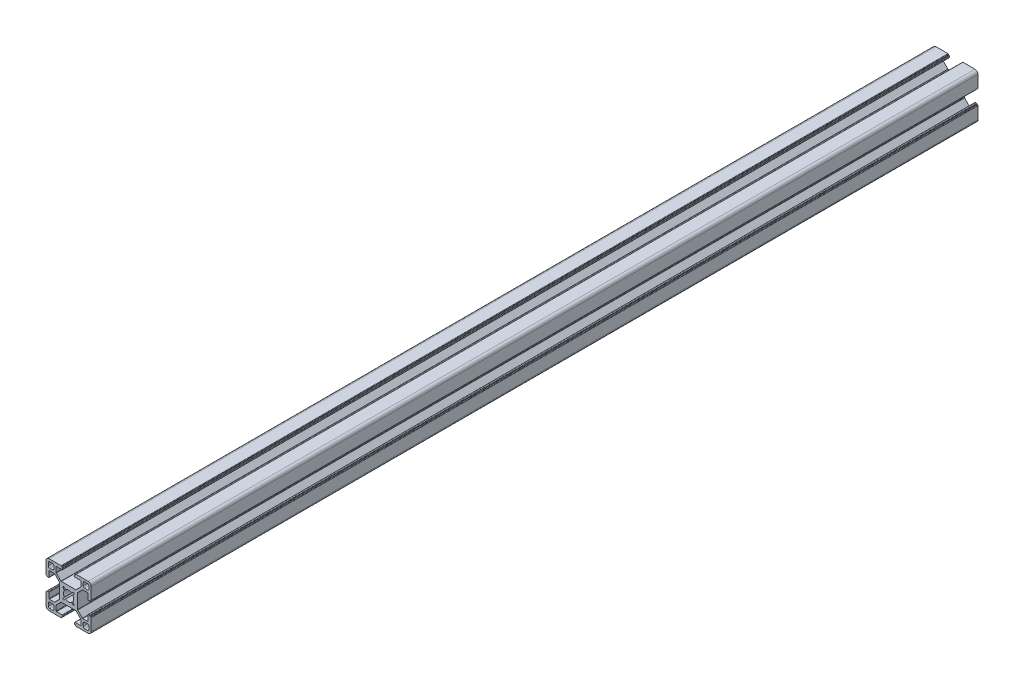
SolidWorks part; units mm, degrees
ref_plane "Piano frontale" through (0, 0, 0) normal (0, 0, 1) x (1, 0, 0)
ref_plane "Piano superiore" through (0, 0, 0) normal (0, 1, 0) x (1, 0, 0)
ref_plane "Piano destro" through (0, 0, 0) normal (1, 0, 0) x (0, 0, -1)
ref_plane "Piano1" through (0, 0, 25) normal (0, 0, 1) x (1, 0, 0)
sketch "Schizzo1" plane through (0, 0, 25) normal (0, 0, 1) x (1, 0, 0)
  line L0 (-12.5625, -9.75) -> (-10.6875, -9.75)
  line L1 (-9.75, -10.6875) -> (-9.75, -12.5625)
  line L2 (-10.6875, -13.5) -> (-12.5625, -13.5)
  line L3 (-13.5, -12.5625) -> (-13.5, -10.6875)
  line L4 (12.5625, 9.75) -> (10.6875, 9.75)
  line L5 (9.75, 10.6875) -> (9.75, 12.5625)
  line L6 (10.6875, 13.5) -> (12.5625, 13.5)
  line L7 (13.5, 12.5625) -> (13.5, 10.6875)
  line L8 (-4.7, -14.7) -> (-4.7, -14.6)
  line L9 (-4.4, -14.3) -> (-4.3, -14.3)
  line L10 (-4, -14) -> (-4, -13.3)
  line L11 (-4.3, -13) -> (-7.95, -13)
  line L12 (-8.25, -12.7) -> (-8.25, -9.4349)
  line L13 (-8.1621, -9.2228) -> (-5.0272, -6.0879)
  line L14 (-4.8151, -6) -> (4.8151, -6)
  line L15 (5.0272, -6.0879) -> (8.1621, -9.2228)
  line L16 (8.25, -9.4349) -> (8.25, -12.7)
  line L17 (7.95, -13) -> (4.3, -13)
  line L18 (4, -13.3) -> (4, -14)
  line L19 (4.3, -14.3) -> (4.4, -14.3)
  line L20 (4.7, -14.6) -> (4.7, -14.7)
  line L21 (5, -15) -> (13, -15)
  line L22 (15, -13) -> (15, -5)
  line L23 (14.7, -4.7) -> (14.6, -4.7)
  line L24 (14.3, -4.4) -> (14.3, -4.3)
  line L25 (14, -4) -> (13.3, -4)
  line L26 (13, -4.3) -> (13, -7.95)
  line L27 (12.7, -8.25) -> (9.4349, -8.25)
  line L28 (9.2228, -8.1621) -> (6.0879, -5.0272)
  line L29 (6, -4.8151) -> (6, 4.8151)
  line L30 (6.0879, 5.0272) -> (9.2228, 8.1621)
  line L31 (9.4349, 8.25) -> (12.7, 8.25)
  line L32 (13, 7.95) -> (13, 4.3)
  line L33 (13.3, 4) -> (14, 4)
  line L34 (14.3, 4.3) -> (14.3, 4.4)
  line L35 (14.6, 4.7) -> (14.7, 4.7)
  line L36 (15, 5) -> (15, 13)
  line L37 (13, 15) -> (5, 15)
  line L38 (4.7, 14.7) -> (4.7, 14.6)
  line L39 (4.4, 14.3) -> (4.3, 14.3)
  line L40 (4, 14) -> (4, 13.3)
  line L41 (4.3, 13) -> (7.95, 13)
  line L42 (8.25, 12.7) -> (8.25, 9.4349)
  line L43 (8.1621, 9.2228) -> (5.0272, 6.0879)
  line L44 (4.8151, 6) -> (-4.8151, 6)
  line L45 (-5.0272, 6.0879) -> (-8.1621, 9.2228)
  line L46 (-8.25, 9.4349) -> (-8.25, 12.7)
  line L47 (-7.95, 13) -> (-4.3, 13)
  line L48 (-4, 13.3) -> (-4, 14)
  line L49 (-4.3, 14.3) -> (-4.4, 14.3)
  line L50 (-4.7, 14.6) -> (-4.7, 14.7)
  line L51 (-5, 15) -> (-13, 15)
  line L52 (-15, 13) -> (-15, 5)
  line L53 (-14.7, 4.7) -> (-14.6, 4.7)
  line L54 (-14.3, 4.4) -> (-14.3, 4.3)
  line L55 (-14, 4) -> (-13.3, 4)
  line L56 (-13, 4.3) -> (-13, 7.95)
  line L57 (-12.7, 8.25) -> (-9.4349, 8.25)
  line L58 (-9.2228, 8.1621) -> (-6.0879, 5.0272)
  line L59 (-6, 4.8151) -> (-6, -4.8151)
  line L60 (-6.0879, -5.0272) -> (-9.2228, -8.1621)
  line L61 (-9.4349, -8.25) -> (-12.7, -8.25)
  line L62 (-13, -7.95) -> (-13, -4.3)
  line L63 (-13.3, -4) -> (-14, -4)
  line L64 (-14.3, -4.3) -> (-14.3, -4.4)
  line L65 (-14.6, -4.7) -> (-14.7, -4.7)
  line L66 (-15, -5) -> (-15, -13)
  line L67 (-13, -15) -> (-5, -15)
  line L68 (2.0101, 2.7422) -> (2.8679, 3.6)
  line L69 (3.6, 2.8679) -> (2.7422, 2.0101)
  line L70 (2.7422, -2.0101) -> (3.6, -2.8679)
  line L71 (2.8679, -3.6) -> (2.0101, -2.7422)
  line L72 (-2.0101, -2.7422) -> (-2.8679, -3.6)
  line L73 (-3.6, -2.8679) -> (-2.7422, -2.0101)
  line L74 (-2.7422, 2.0101) -> (-3.6, 2.8679)
  line L75 (-2.8679, 3.6) -> (-2.0101, 2.7422)
  line L76 (-9.75, 12.5625) -> (-9.75, 10.6875)
  line L77 (-10.6875, 9.75) -> (-12.5625, 9.75)
  line L78 (-13.5, 10.6875) -> (-13.5, 12.5625)
  line L79 (-12.5625, 13.5) -> (-10.6875, 13.5)
  line L80 (9.75, -12.5625) -> (9.75, -10.6875)
  line L81 (10.6875, -9.75) -> (12.5625, -9.75)
  line L82 (13.5, -10.6875) -> (13.5, -12.5625)
  line L83 (12.5625, -13.5) -> (10.6875, -13.5)
  arc A0 (-10.6875, -9.75) -> (-9.75, -10.6875) centre (-10.6875, -10.6875) cw
  arc A1 (-9.75, -12.5625) -> (-10.6875, -13.5) centre (-10.6875, -12.5625) cw
  arc A2 (-12.5625, -13.5) -> (-13.5, -12.5625) centre (-12.5625, -12.5625) cw
  arc A3 (-13.5, -10.6875) -> (-12.5625, -9.75) centre (-12.5625, -10.6875) cw
  arc A4 (10.6875, 9.75) -> (9.75, 10.6875) centre (10.6875, 10.6875) cw
  arc A5 (9.75, 12.5625) -> (10.6875, 13.5) centre (10.6875, 12.5625) cw
  arc A6 (12.5625, 13.5) -> (13.5, 12.5625) centre (12.5625, 12.5625) cw
  arc A7 (13.5, 10.6875) -> (12.5625, 9.75) centre (12.5625, 10.6875) cw
  arc A8 (-5, -15) -> (-4.7, -14.7) centre (-5, -14.7) ccw
  arc A9 (-4.7, -14.6) -> (-4.4, -14.3) centre (-4.4, -14.6) cw
  arc A10 (-4.3, -14.3) -> (-4, -14) centre (-4.3, -14) ccw
  arc A11 (-4, -13.3) -> (-4.3, -13) centre (-4.3, -13.3) ccw
  arc A12 (-7.95, -13) -> (-8.25, -12.7) centre (-7.95, -12.7) cw
  arc A13 (-8.25, -9.4349) -> (-8.1621, -9.2228) centre (-7.95, -9.4349) cw
  arc A14 (-5.0272, -6.0879) -> (-4.8151, -6) centre (-4.8151, -6.3) cw
  arc A15 (4.8151, -6) -> (5.0272, -6.0879) centre (4.8151, -6.3) cw
  arc A16 (8.1621, -9.2228) -> (8.25, -9.4349) centre (7.95, -9.4349) cw
  arc A17 (8.25, -12.7) -> (7.95, -13) centre (7.95, -12.7) cw
  arc A18 (4.3, -13) -> (4, -13.3) centre (4.3, -13.3) ccw
  arc A19 (4, -14) -> (4.3, -14.3) centre (4.3, -14) ccw
  arc A20 (4.4, -14.3) -> (4.7, -14.6) centre (4.4, -14.6) cw
  arc A21 (4.7, -14.7) -> (5, -15) centre (5, -14.7) ccw
  arc A22 (13, -15) -> (15, -13) centre (13, -13) ccw
  arc A23 (15, -5) -> (14.7, -4.7) centre (14.7, -5) ccw
  arc A24 (14.6, -4.7) -> (14.3, -4.4) centre (14.6, -4.4) cw
  arc A25 (14.3, -4.3) -> (14, -4) centre (14, -4.3) ccw
  arc A26 (13.3, -4) -> (13, -4.3) centre (13.3, -4.3) ccw
  arc A27 (13, -7.95) -> (12.7, -8.25) centre (12.7, -7.95) cw
  arc A28 (9.4349, -8.25) -> (9.2228, -8.1621) centre (9.4349, -7.95) cw
  arc A29 (6.0879, -5.0272) -> (6, -4.8151) centre (6.3, -4.8151) cw
  arc A30 (6, 4.8151) -> (6.0879, 5.0272) centre (6.3, 4.8151) cw
  arc A31 (9.2228, 8.1621) -> (9.4349, 8.25) centre (9.4349, 7.95) cw
  arc A32 (12.7, 8.25) -> (13, 7.95) centre (12.7, 7.95) cw
  arc A33 (13, 4.3) -> (13.3, 4) centre (13.3, 4.3) ccw
  arc A34 (14, 4) -> (14.3, 4.3) centre (14, 4.3) ccw
  arc A35 (14.3, 4.4) -> (14.6, 4.7) centre (14.6, 4.4) cw
  arc A36 (14.7, 4.7) -> (15, 5) centre (14.7, 5) ccw
  arc A37 (15, 13) -> (13, 15) centre (13, 13) ccw
  arc A38 (5, 15) -> (4.7, 14.7) centre (5, 14.7) ccw
  arc A39 (4.7, 14.6) -> (4.4, 14.3) centre (4.4, 14.6) cw
  arc A40 (4.3, 14.3) -> (4, 14) centre (4.3, 14) ccw
  arc A41 (4, 13.3) -> (4.3, 13) centre (4.3, 13.3) ccw
  arc A42 (7.95, 13) -> (8.25, 12.7) centre (7.95, 12.7) cw
  arc A43 (8.25, 9.4349) -> (8.1621, 9.2228) centre (7.95, 9.4349) cw
  arc A44 (5.0272, 6.0879) -> (4.8151, 6) centre (4.8151, 6.3) cw
  arc A45 (-4.8151, 6) -> (-5.0272, 6.0879) centre (-4.8151, 6.3) cw
  arc A46 (-8.1621, 9.2228) -> (-8.25, 9.4349) centre (-7.95, 9.4349) cw
  arc A47 (-8.25, 12.7) -> (-7.95, 13) centre (-7.95, 12.7) cw
  arc A48 (-4.3, 13) -> (-4, 13.3) centre (-4.3, 13.3) ccw
  arc A49 (-4, 14) -> (-4.3, 14.3) centre (-4.3, 14) ccw
  arc A50 (-4.4, 14.3) -> (-4.7, 14.6) centre (-4.4, 14.6) cw
  arc A51 (-4.7, 14.7) -> (-5, 15) centre (-5, 14.7) ccw
  arc A52 (-13, 15) -> (-15, 13) centre (-13, 13) ccw
  arc A53 (-15, 5) -> (-14.7, 4.7) centre (-14.7, 5) ccw
  arc A54 (-14.6, 4.7) -> (-14.3, 4.4) centre (-14.6, 4.4) cw
  arc A55 (-14.3, 4.3) -> (-14, 4) centre (-14, 4.3) ccw
  arc A56 (-13.3, 4) -> (-13, 4.3) centre (-13.3, 4.3) ccw
  arc A57 (-13, 7.95) -> (-12.7, 8.25) centre (-12.7, 7.95) cw
  arc A58 (-9.4349, 8.25) -> (-9.2228, 8.1621) centre (-9.4349, 7.95) cw
  arc A59 (-6.0879, 5.0272) -> (-6, 4.8151) centre (-6.3, 4.8151) cw
  arc A60 (-6, -4.8151) -> (-6.0879, -5.0272) centre (-6.3, -4.8151) cw
  arc A61 (-9.2228, -8.1621) -> (-9.4349, -8.25) centre (-9.4349, -7.95) cw
  arc A62 (-12.7, -8.25) -> (-13, -7.95) centre (-12.7, -7.95) cw
  arc A63 (-13, -4.3) -> (-13.3, -4) centre (-13.3, -4.3) ccw
  arc A64 (-14, -4) -> (-14.3, -4.3) centre (-14, -4.3) ccw
  arc A65 (-14.3, -4.4) -> (-14.6, -4.7) centre (-14.6, -4.4) cw
  arc A66 (-14.7, -4.7) -> (-15, -5) centre (-14.7, -5) ccw
  arc A67 (-15, -13) -> (-13, -15) centre (-13, -13) ccw
  arc A68 (2.8679, 3.6) -> (3.6, 2.8679) centre (3.234, 3.234) cw
  arc A69 (2.7422, 2.0101) -> (2.7422, -2.0101) centre (0, 0) cw
  arc A70 (3.6, -2.8679) -> (2.8679, -3.6) centre (3.234, -3.234) cw
  arc A71 (2.0101, -2.7422) -> (-2.0101, -2.7422) centre (0, 0) cw
  arc A72 (-2.8679, -3.6) -> (-3.6, -2.8679) centre (-3.234, -3.234) cw
  arc A73 (-2.7422, -2.0101) -> (-2.7422, 2.0101) centre (0, 0) cw
  arc A74 (-3.6, 2.8679) -> (-2.8679, 3.6) centre (-3.234, 3.234) cw
  arc A75 (-2.0101, 2.7422) -> (2.0101, 2.7422) centre (0, 0) cw
  arc A76 (-9.75, 10.6875) -> (-10.6875, 9.75) centre (-10.6875, 10.6875) cw
  arc A77 (-12.5625, 9.75) -> (-13.5, 10.6875) centre (-12.5625, 10.6875) cw
  arc A78 (-13.5, 12.5625) -> (-12.5625, 13.5) centre (-12.5625, 12.5625) cw
  arc A79 (-10.6875, 13.5) -> (-9.75, 12.5625) centre (-10.6875, 12.5625) cw
  arc A80 (9.75, -10.6875) -> (10.6875, -9.75) centre (10.6875, -10.6875) cw
  arc A81 (12.5625, -9.75) -> (13.5, -10.6875) centre (12.5625, -10.6875) cw
  arc A82 (13.5, -12.5625) -> (12.5625, -13.5) centre (12.5625, -12.5625) cw
  arc A83 (10.6875, -13.5) -> (9.75, -12.5625) centre (10.6875, -12.5625) cw
extrude "Estrusione-Estrusione1" add sketch "Schizzo1" against normal blind 590
